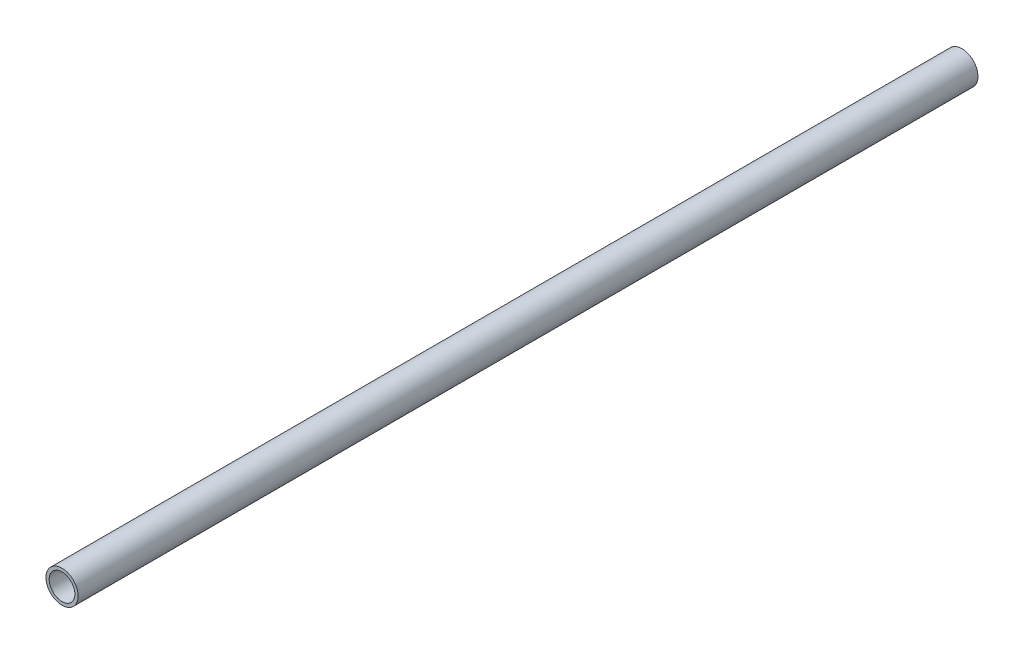
SolidWorks part; units mm, degrees
material "Thornel Mat VMA"
ref_plane "Front Plane" through (0, 0, 0) normal (0, 0, 1) x (1, 0, 0)
ref_plane "Top Plane" through (0, 0, 0) normal (0, 1, 0) x (1, 0, 0)
ref_plane "Right Plane" through (0, 0, 0) normal (1, 0, 0) x (0, 0, -1)
sketch "Sketch1" plane through (0, 0, 0) normal (0, 0, 1) x (1, 0, 0)
  circle A0 centre (0, 0) radius 5
sketch "Sketch2" plane through (0, 0, 0) normal (0, 0, 1) x (1, 0, 0)
  circle A0 centre (0, 0) radius 4
ref_plane "Plane1" through (0, 0, 280) normal (0, 0, 1) x (1, 0, 0)
sketch "Sketch3" plane through (0, 0, 280) normal (0, 0, 1) x (1, 0, 0)
  circle A0 centre (0, 0) radius 5
loft "Loft1" add profiles "Sketch1", "Sketch3"
extrude "Cut-Extrude1" cut sketch "Sketch2" along normal blind 326
